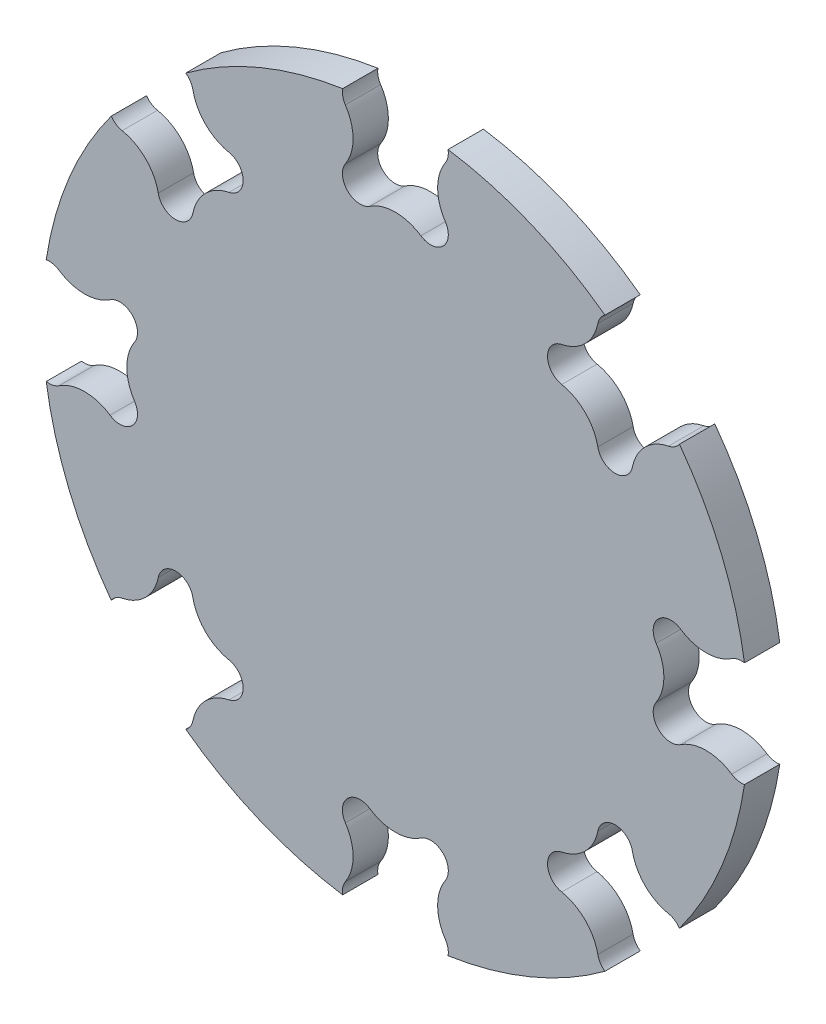
SolidWorks part; units mm, degrees
ref_plane "前基準面" through (0, 0, 0) normal (0, 0, 1) x (1, 0, 0)
ref_plane "上基準面" through (0, 0, 0) normal (0, 1, 0) x (1, 0, 0)
ref_plane "右基準面" through (0, 0, 0) normal (1, 0, 0) x (0, 0, -1)
sketch "草圖1" plane through (0, 0, 0) normal (0, 0, 1) x (1, 0, 0)
  circle A0 centre (0, 0) radius 100
  dimension "D1" = 200
extrude "伸長1" add sketch "草圖1" along normal blind 10
sketch "草圖2" plane through (0, 0, 0) normal (0, 0, 1) x (1, 0, 0)
  line L0 (0, 0) -> (12.6556, 0) construction
  line L2 (0, 88.0278) -> (20.7646, 88.0278) construction
  line L3 (0, 118.1003) -> (0, 0) construction
  arc A0 (14.1603, 95.2543) -> (14.1603, 80.8013) centre (25, 88.0278) ccw
  arc A1 (-7.2265, 102.188) -> (7.2265, 102.188) centre (0, 113.0278) ccw
  arc A2 (7.2265, 102.188) -> (14.1603, 95.2543) centre (10, 98.0278) cw
  arc A3 (7.2265, 73.8675) -> (14.1603, 80.8013) centre (10, 78.0278) ccw
  arc A4 (-7.2265, 102.188) -> (-14.1603, 95.2543) centre (-10, 98.0278) ccw
  arc A5 (-7.2265, 73.8675) -> (-14.1603, 80.8013) centre (-10, 78.0278) cw
  arc A6 (-14.1603, 95.2543) -> (-14.1603, 80.8013) centre (-25, 88.0278) cw
  arc A7 (-7.2265, 73.8675) -> (7.2265, 73.8675) centre (0, 63.0278) cw
  circle A9 centre (0, 0) radius 100 construction
  dimension "D1" = 5
  dimension "D3" = 10
  dimension "D6" = 25
  dimension "D4" = 10
  dimension "D5" = 25
extrude "伸長5" cut sketch "草圖2" along normal through all
pattern_circular "環狀複製排列1" count 8 over 360 about axis through (0, 0, 0) along (0, 0, 1) of "伸長5"
